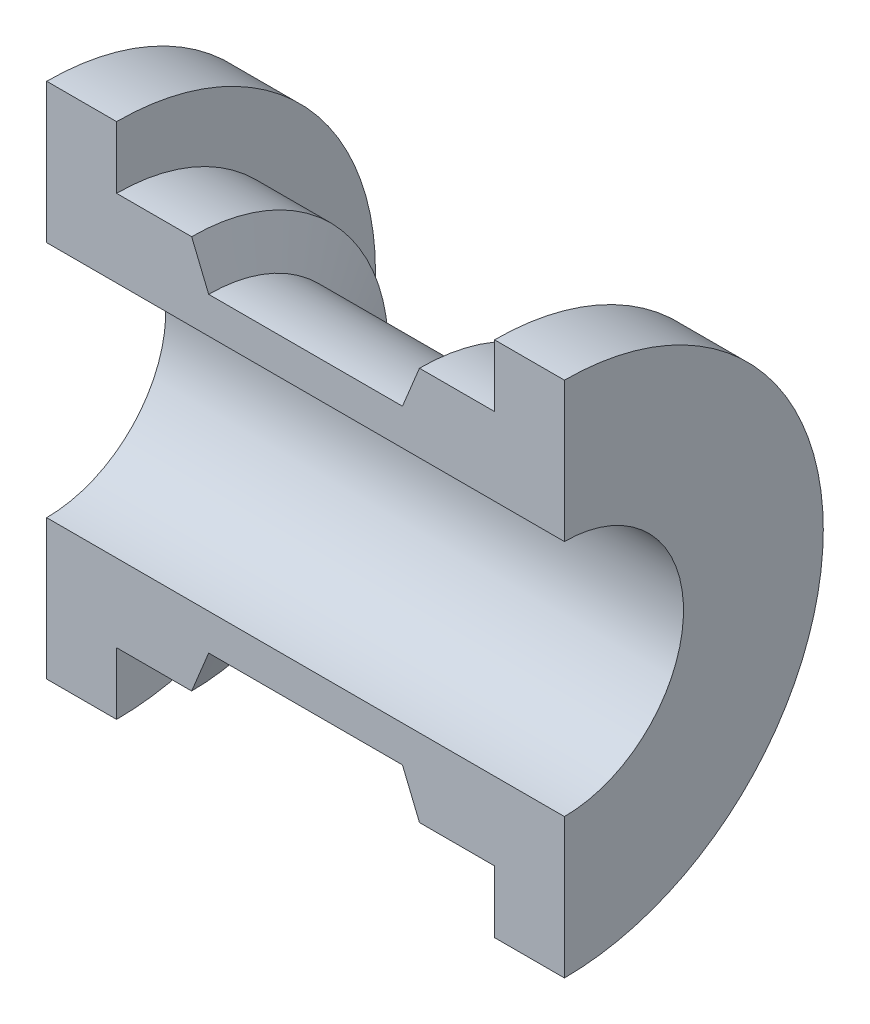
SolidWorks part; units mm, degrees
ref_plane "Front Plane" through (0, 0, 0) normal (0, 0, 1) x (1, 0, 0)
ref_plane "Top Plane" through (0, 0, 0) normal (0, 1, 0) x (1, 0, 0)
ref_plane "Right Plane" through (0, 0, 0) normal (1, 0, 0) x (0, 0, -1)
sketch "Sketch1" plane through (0, 0, 0) normal (0, 0, 1) x (1, 0, 0)
  line L0 (-25, -11.5) -> (25, -11.5)
  line L1 (25, -11.5) -> (25, -25)
  line L2 (25, -25) -> (18.25, -25)
  line L3 (18.25, -25) -> (18.25, -19)
  line L4 (18.25, -19) -> (11, -19)
  line L5 (11, -19) -> (9.3573, -15)
  line L6 (9.3573, -15) -> (-9.3573, -15)
  line L7 (-9.3573, -15) -> (-11, -19)
  line L8 (-11, -19) -> (-18.25, -19)
  line L9 (-18.25, -19) -> (-18.25, -25)
  line L10 (-18.25, -25) -> (-25, -25)
  line L11 (-25, -25) -> (-25, -11.5)
  line L12 (-23.879, 0) -> (26.0883, 0) construction
  point P2 (0, -11.5)
  point P16 (10.3346, -15)
  dimension "D1" = 50
  dimension "D2" = 22
  dimension "D3" = 36.5
  dimension "D4" = 11.5
  dimension "D5" = 25
  dimension "D6" = 15
  dimension "D7" = 19
revolve "Revolve1" add sketch "Sketch1" angle 180 about L12
sketch "Sketch2" plane through (0, 0, 0) normal (0, 1, 0) x (1, 0, 0)
  line L0 (0, 0) -> (0, 12.2463) construction
  line L4 (-3, 20) -> (0, 20)
  line L6 (-3, 20) -> (-3, 12.2463)
  line L7 (-3, 12.2463) -> (0, 12.2463)
  line L9 (0, 12.2463) -> (0, 20)
  dimension "D1" = 3
revolve "Revolve2" add sketch "Sketch2" angle 360 about L0
